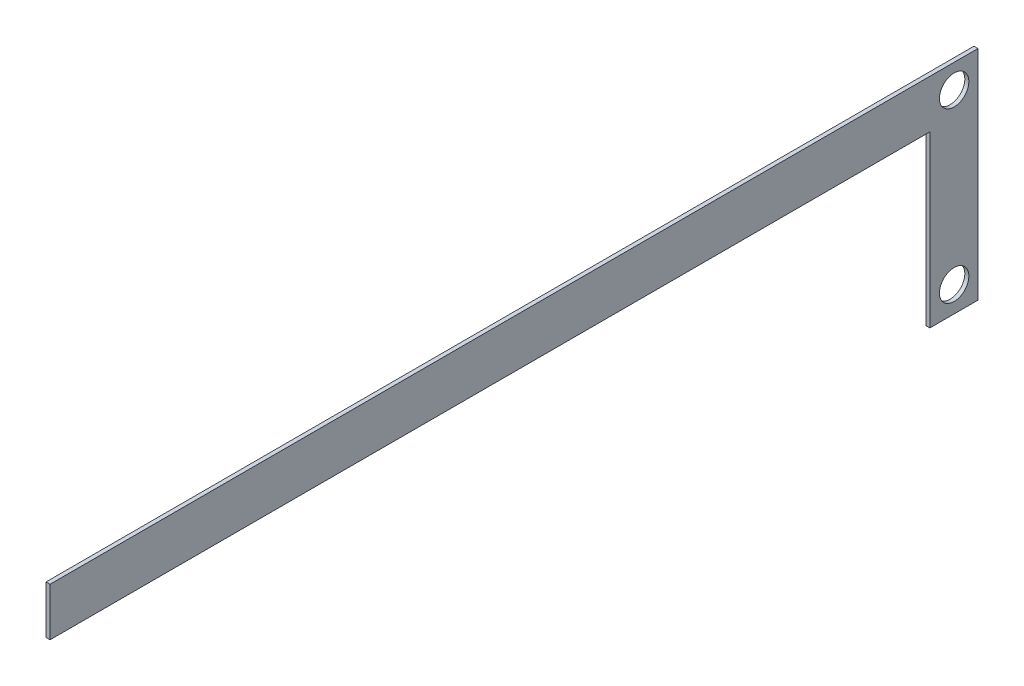
SolidWorks part; units mm, degrees
ref_plane "Front Plane" through (0, 0, 0) normal (0, 0, 1) x (1, 0, 0)
ref_plane "Top Plane" through (0, 0, 0) normal (0, 1, 0) x (1, 0, 0)
ref_plane "Right Plane" through (0, 0, 0) normal (1, 0, 0) x (0, 0, -1)
sketch "Sketch2" plane through (0, 0, 0) normal (1, 0, 0) x (0, 0, -1)
  line L0 (0, 0) -> (0, 3.6)
  line L1 (0, 3.6) -> (69.4, 3.6)
  line L2 (69.4, 3.6) -> (69.4, -12.7)
  line L3 (69.4, -12.7) -> (65.8, -12.7)
  line L4 (65.8, -12.7) -> (65.8, 0)
  line L5 (65.8, 0) -> (0, 0)
  dimension "D1" = 3.6
  dimension "D2" = 3.6
  dimension "D3" = 69.4
  dimension "D4" = 16.3
extrude "Boss-Extrude1" add sketch "Sketch2" along normal blind 0.3
sketch "Sketch3" plane through (0.3, 0, 0) normal (1, 0, 0) x (0, 0, -1)
  line L0 (69.4, -12.7) -> (69.4, 3.6) construction
  line L1 (69.4, 3.6) -> (0, 3.6) construction
  line L2 (65.8, -12.7) -> (69.4, -12.7) construction
  circle A0 centre (67.6145, 1.805) radius 1.1
  circle A1 centre (67.6145, -10.795) radius 1.1
  point P4 (0, 0)
  dimension "D1" = 2.2
  dimension "D2" = 2.2
  dimension "D3" = 1.7855
  dimension "D4" = 1.7855
  dimension "D5" = 1.795
  dimension "D6" = 1.905
extrude "Cut-Extrude5" cut sketch "Sketch3" against normal blind 0.3
